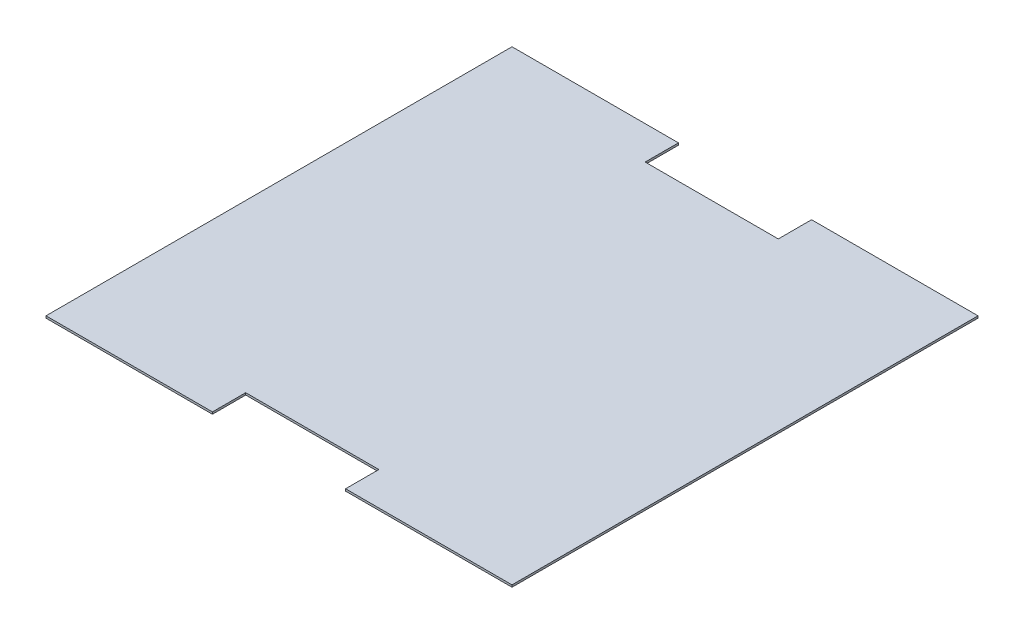
SolidWorks part; units mm, degrees
material "1060 Alloy"
ref_plane "Front Plane" through (0, 0, 0) normal (0, 0, 1) x (1, 0, 0)
ref_plane "Top Plane" through (0, 0, 0) normal (0, 1, 0) x (1, 0, 0)
ref_plane "Right Plane" through (0, 0, 0) normal (1, 0, 0) x (0, 0, -1)
sketch "Sketch1" plane through (0, 0, 0) normal (0, 1, 0) x (1, 0, 0)
  line L1 (337.7346, 267.1998) -> (1048.9346, 267.1998)
  line L2 (337.7346, 267.1998) -> (337.7346, -444.0002)
  line L3 (337.7346, -444.0002) -> (1048.9346, -444.0002)
  line L4 (1048.9346, 267.1998) -> (1048.9346, -444.0002)
extrude "Boss-Extrude1" add sketch "Sketch1" along normal blind 3.175
sketch "Sketch2" plane through (0, 3.175, 0) normal (0, 1, 0) x (1, 0, 0)
  line L0 (1048.9346, 267.1998) -> (337.7346, 267.1998) construction
  line L1 (591.7346, 267.1998) -> (794.9346, 267.1998)
  line L2 (591.7346, 267.1998) -> (591.7346, 216.3998)
  line L3 (591.7346, 216.3998) -> (794.9346, 216.3998)
  line L4 (794.9346, 267.1998) -> (794.9346, 216.3998)
  line L5 (337.7346, -444.0002) -> (1048.9346, -444.0002) construction
  line L6 (591.7346, -444.0002) -> (794.9346, -444.0002)
  line L7 (591.7346, -444.0002) -> (591.7346, -393.2002)
  line L8 (591.7346, -393.2002) -> (794.9346, -393.2002)
  line L9 (794.9346, -444.0002) -> (794.9346, -393.2002)
  line L10 (337.7346, 267.1998) -> (337.7346, -444.0002) construction
  line L11 (1048.9346, -444.0002) -> (1048.9346, 267.1998) construction
  dimension "D1" = 254
  dimension "D2" = 254
  dimension "D3" = 254
  dimension "D4" = 254
  dimension "D5" = 50.8
  dimension "D6" = 50.8
extrude "Cut-Extrude1" cut sketch "Sketch2" against normal through all
